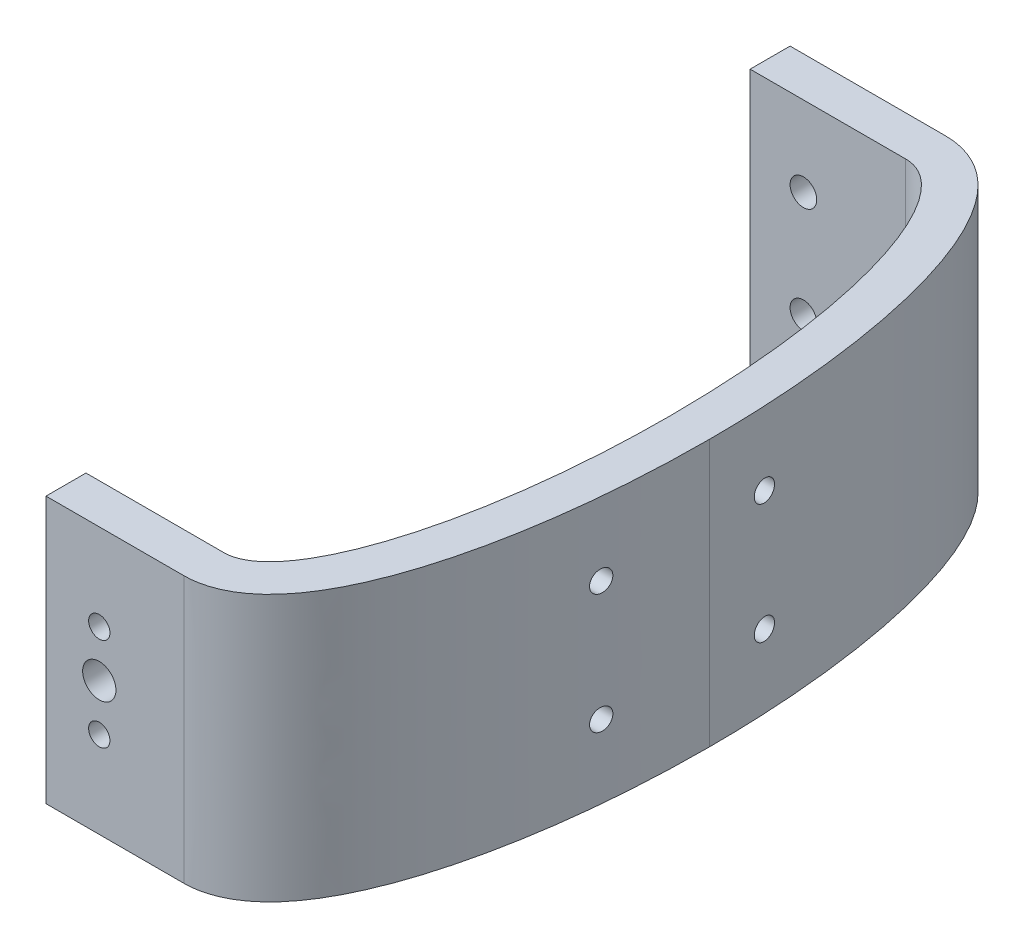
SolidWorks part; units mm, degrees
ref_plane "前视基准面" through (0, 0, 0) normal (0, 0, 1) x (1, 0, 0)
ref_plane "上视基准面" through (0, 0, 0) normal (0, 1, 0) x (1, 0, 0)
ref_plane "右视基准面" through (0, 0, 0) normal (1, 0, 0) x (0, 0, -1)
other "Configuration Table"
sketch3d "3D草图1"
  point P0 (0, 20, 0)
  point P1 (10, 20, 0)
  point P2 (0, 20, 10)
ref_plane "基准面1" through (0, 20, 0) normal (0, -1, 0) x (-1, 0, 0)
sketch "草图1" plane through (0, 20, 0) normal (0, -1, 0) x (-1, 0, 0)
  line L0 (-222.2784, 60.7185) -> (-222.2784, 54.7185)
  line L1 (-222.2784, -47.6561) -> (-222.2784, -53.6561)
  spline S0 degree 8 poles (-222.2784, -53.6561) (-223.1803, -53.6561) (-224.0793, -53.5711) (-224.9608, -53.4016) (-225.8092, -53.1544) (-226.6156, -52.8411) (-227.3774, -52.4737) (-228.8143, -51.6481) (-230.0882, -50.6677) (-230.6871, -50.1456) (-231.2524, -49.596) (-231.7882, -49.0215) (-232.2984, -48.4233) (-233.7606, -46.5604) (-235.0407, -44.4962) (-235.8332, -43.034) (-236.5757, -41.4844) (-237.2741, -39.8472) (-237.9316, -38.1237) (-239.7875, -32.6994) (-241.3011, -26.5349) (-242.1653, -22.1152) (-242.8763, -17.4142) (-243.4265, -12.4645) (-243.8048, -7.3) (-244, -1.9561) (-244, 3.5312) knots 0 0 0 0 0 0 0 0 0 0.125 0.125 0.125 0.125 0.125 0.125 0.25 0.25 0.25 0.25 0.25 0.25 0.5 0.5 0.5 0.5 0.5 0.5 1 1 1 1 1 1 1 1 1
  spline S1 degree 8 poles (-244, 3.5312) (-244, 9.0186) (-243.8048, 14.3624) (-243.4265, 19.5269) (-242.8763, 24.4767) (-242.1653, 29.1776) (-241.3011, 33.5973) (-239.7875, 39.7619) (-237.9316, 45.1862) (-237.2741, 46.9096) (-236.5757, 48.5468) (-235.8332, 50.0965) (-235.0407, 51.5586) (-233.7606, 53.6228) (-232.2984, 55.4858) (-231.7882, 56.0839) (-231.2524, 56.6585) (-230.6871, 57.208) (-230.0882, 57.7301) (-228.8143, 58.7105) (-227.3774, 59.5362) (-226.6156, 59.9035) (-225.8092, 60.2168) (-224.9608, 60.464) (-224.0793, 60.6335) (-223.1803, 60.7185) (-222.2784, 60.7185) knots 0 0 0 0 0 0 0 0 0 0.5 0.5 0.5 0.5 0.5 0.5 0.75 0.75 0.75 0.75 0.75 0.75 0.875 0.875 0.875 0.875 0.875 0.875 1 1 1 1 1 1 1 1 1
  spline S2 degree 3 poles (-222.2784, 54.7185) (-230.9612, 54.7185) (-238, 31.8012) (-238, 3.5312) knots 0 0 0 0 1 1 1 1
  spline S3 degree 3 poles (-238, 3.5312) (-238, -24.7387) (-230.9612, -47.6561) (-222.2784, -47.6561) knots 0 0 0 0 1 1 1 1
extrude "凸台-拉伸1" add sketch "草图1" along normal blind 40
sketch3d "3D草图2"
  point P0 (0, 0, 47.6561)
  point P1 (10, 0, 47.6561)
  point P2 (0, 10, 47.6561)
ref_plane "基准面2" through (0, 0, 47.6561) normal (0, 0, 1) x (1, 0, 0)
sketch "草图2" plane through (0, 0, 47.6561) normal (0, 0, 1) x (1, 0, 0)
  line L0 (201.5786, -20) -> (222.2784, -20)
  line L1 (222.2784, -20) -> (222.2784, 20)
  line L2 (222.2784, 20) -> (201.5786, 20)
  line L3 (201.5786, 20) -> (201.5786, -20)
extrude "凸台-拉伸2" add sketch "草图2" along normal blind 6
sketch3d "3D草图3"
  point P0 (0, 0, -60.7185)
  point P1 (10, 0, -60.7185)
  point P2 (0, 10, -60.7185)
ref_plane "基准面3" through (0, 0, -60.7185) normal (0, 0, 1) x (1, 0, 0)
sketch "草图3" plane through (0, 0, -60.7185) normal (0, 0, 1) x (1, 0, 0)
  line L0 (198.9229, -20) -> (222.2784, -20)
  line L1 (222.2784, -20) -> (222.2784, 20)
  line L2 (222.2784, 20) -> (198.9229, 20)
  line L3 (198.9229, 20) -> (198.9229, -20)
extrude "凸台-拉伸3" add sketch "草图3" along normal blind 6
sketch3d "3D草图4"
  point P0 (0, 0, 47.6561)
  point P1 (10, 0, 47.6561)
  point P2 (0, 10, 47.6561)
ref_plane "基准面4" through (0, 0, 47.6561) normal (0, 0, 1) x (1, 0, 0)
sketch "草图4" plane through (0, 0, 47.6561) normal (0, 0, 1) x (1, 0, 0)
  circle A0 centre (209.5786, -7) radius 1.6
  circle A1 centre (209.5786, 7) radius 1.6
  circle A2 centre (209.5786, 0) radius 2.5
extrude "切除-拉伸1" cut sketch "草图4" along normal blind 6
sketch3d "3D草图5"
  point P0 (0, 0, -60.7185)
  point P1 (10, 0, -60.7185)
  point P2 (0, 10, -60.7185)
ref_plane "基准面5" through (0, 0, -60.7185) normal (0, 0, 1) x (1, 0, 0)
sketch "草图5" plane through (0, 0, -60.7185) normal (0, 0, 1) x (1, 0, 0)
  circle A0 centre (206.9229, -8) radius 2
  circle A1 centre (206.9229, 8) radius 2
extrude "切除-拉伸2" cut sketch "草图5" along normal blind 6
sketch3d "3D草图6"
  point P0 (285, 0, 0)
  point P1 (285, 10, 0)
  point P2 (285, 0, 10)
ref_plane "基准面6" through (285, 0, 0) normal (1, 0, 0) x (0, 0, -1)
sketch "草图6" plane through (285, 0, 0) normal (1, 0, 0) x (0, 0, -1)
  circle A0 centre (12, -9) radius 1.6
  circle A1 centre (-12, -9) radius 1.6
  circle A2 centre (12, 9) radius 1.6
  circle A3 centre (-12, 9) radius 1.6
extrude "切除-拉伸3" cut sketch "草图6" against normal blind 50
sketch3d "3D草图7"
  point P0 (230, 0, 0)
  point P1 (230, 10, 0)
  point P2 (230, 0, 10)
ref_plane "基准面7" through (230, 0, 0) normal (1, 0, 0) x (0, 0, -1)
sketch "草图7" plane through (230, 0, 0) normal (1, 0, 0) x (0, 0, -1)
  circle A0 centre (12, -9) radius 3
  circle A1 centre (-12, -9) radius 3
  circle A2 centre (12, 9) radius 3
  circle A3 centre (-12, 9) radius 3
extrude "切除-拉伸4" cut sketch "草图7" along normal blind 8.5
